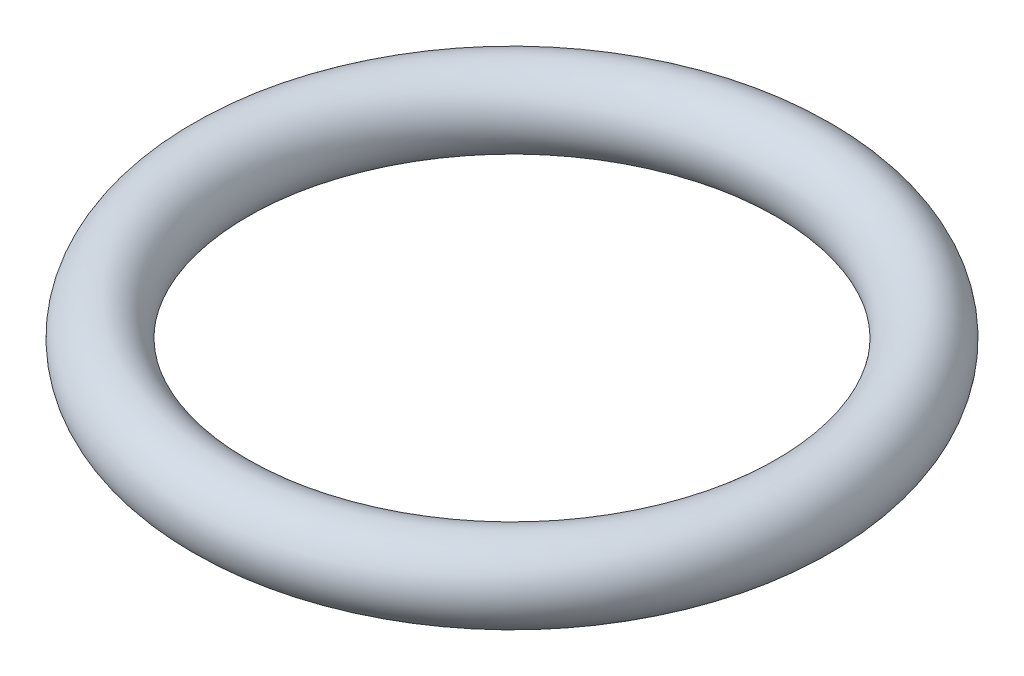
SolidWorks part; units mm, degrees
material "NBR"
ref_plane "Ön Düzlem" through (0, 0, 0) normal (0, 0, 1) x (1, 0, 0)
ref_plane "Üst Düzlem" through (0, 0, 0) normal (0, 1, 0) x (1, 0, 0)
ref_plane "Sağ Düzlem" through (0, 0, 0) normal (1, 0, 0) x (0, 0, -1)
sketch "Çizim1" plane through (0, 0, 0) normal (0, 0, 1) x (1, 0, 0)
  line L1 (0, 0) -> (0, 13.2033)
  circle A0 centre (-13.465, 0) radius 1.765
  dimension "D1" = 3.53
revolve "Döndür1" add sketch "Çizim1" angle 360 about L1
sketch "Çizim2" plane through (0, 0, 0) normal (0, 1, 0) x (1, 0, 0)
  circle A0 centre (0, 0) radius 25.1965
sketch "Çizim3" plane through (0, 0, 0) normal (0, 0, 1) x (1, 0, 0)
  line L0 (-13.1103, 1.765) -> (12.7542, 1.765)
  line L1 (13.465, 1.765) -> (-13.465, 1.765) construction
